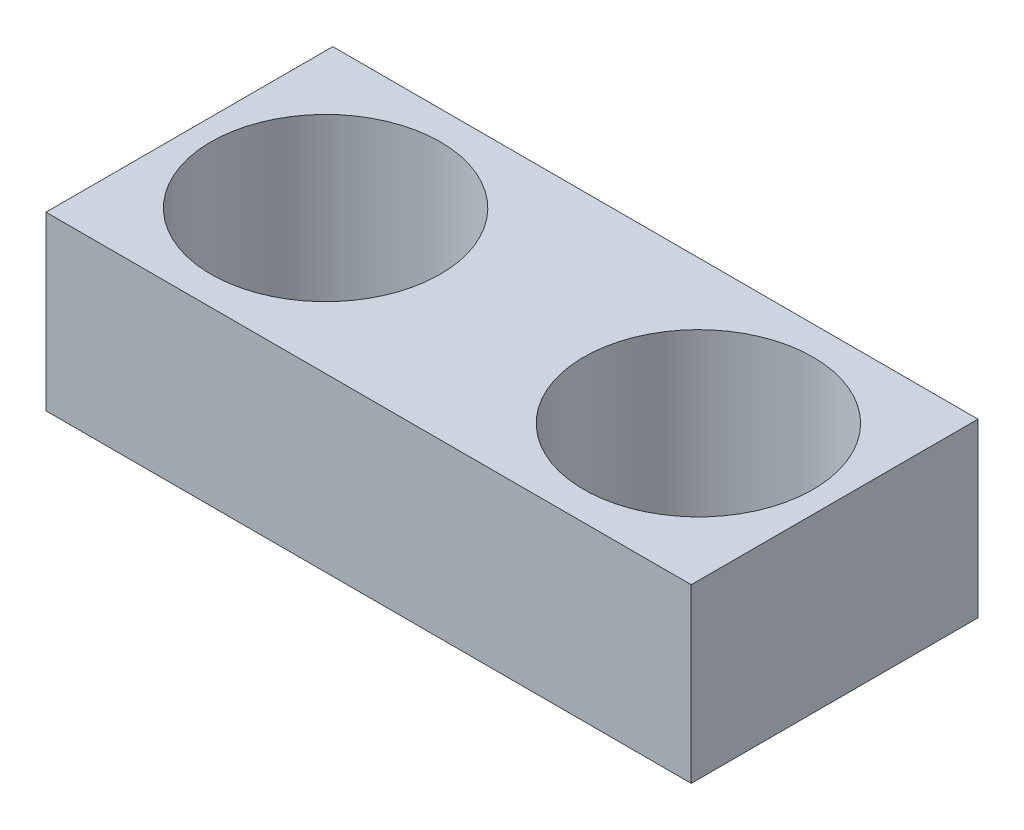
SolidWorks part; units mm, degrees
ref_plane "Front Plane" through (0, 0, 0) normal (0, 0, 1) x (1, 0, 0)
ref_plane "Top Plane" through (0, 0, 0) normal (0, 1, 0) x (1, 0, 0)
ref_plane "Right Plane" through (0, 0, 0) normal (1, 0, 0) x (0, 0, -1)
sketch "Sketch1" plane through (0, 0, 0) normal (0, 1, 0) x (1, 0, 0)
  line L1 (0, 0) -> (-45, 0)
  line L2 (0, 0) -> (0, 20)
  line L3 (0, 20) -> (-45, 20)
  line L4 (-45, 0) -> (-45, 20)
  dimension "D1" = 45
  dimension "D2" = 20
extrude "Boss-Extrude2" add sketch "Sketch1" along normal blind 12 contours L4 L3 L2 L1
sketch "Sketch3" plane through (0, 0, 0) normal (0, -1, 0) x (1, 0, 0)
  line L0 (-45, -10) -> (0, -10) construction
  line L1 (-22.5, 0) -> (-22.5, -20) construction
  line L2 (0, -20) -> (-45, -20) construction
  line L3 (-45, 0) -> (-45, -20) construction
  line L4 (0, 0) -> (0, -20) construction
  line L5 (0, 0) -> (-45, 0) construction
  circle A0 centre (-9.5, -10) radius 8
  circle A1 centre (-35.5, -10) radius 8
  point P17 (-17.5, -10)
  point P18 (-27.5, -10)
  dimension "D2" = 16
  dimension "D3" = 16
  dimension "D1" = 10
extrude "Cut-Extrude1" cut sketch "Sketch3" against normal through all
sketch "Sketch5" plane through (0, 0, 0) normal (0, -1, 0) x (1, 0, 0)
  line L0 (0, -20) -> (-45, -20) construction
  line L1 (-18.1408, -15.5) -> (-26.6109, -15.5)
  line L2 (-18.1408, -20) -> (-26.3592, -20)
  arc A0 (-18.1408, -20) -> (-18.1408, -15.5) centre (-18.9465, -17.75) ccw
  arc A1 (-18.1608, -19.9042) -> (-18.1408, -20) centre (-18.1408, -19.95) ccw construction
  arc A2 (-26.3592, -20) -> (-26.6109, -15.5) centre (-25.7364, -17.7081) cw
  arc A3 (-26.3592, -20) -> (-26.3392, -19.9042) centre (-26.3592, -19.95) ccw construction
extrude "Cut-Extrude2" cut sketch "Sketch5" against normal blind 4 contours A0 L1 A2 L2
